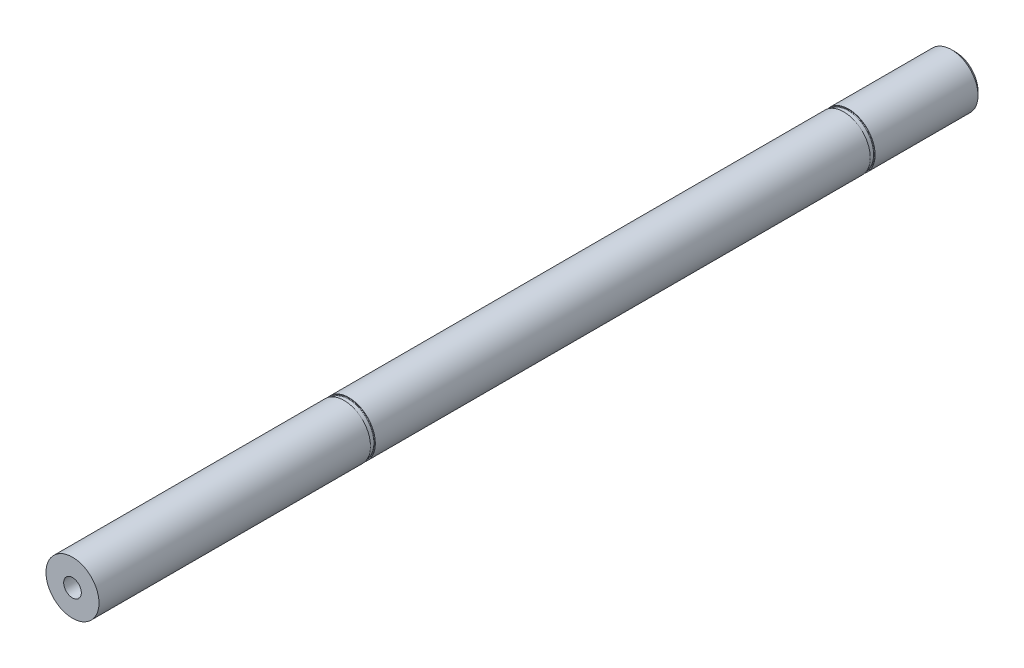
SolidWorks part; units mm, degrees
material "AISI 1045 Steel, cold drawn"
ref_plane "Front" through (0, 0, 0) normal (0, 0, 1) x (1, 0, 0)
ref_plane "Top" through (0, 0, 0) normal (0, 1, 0) x (1, 0, 0)
ref_plane "Right" through (0, 0, 0) normal (1, 0, 0) x (0, 0, -1)
sketch "Sketch1" plane through (0, 0, 0) normal (0, 0, 1) x (1, 0, 0)
  circle A0 centre (0, 0) radius 6
  dimension "OD" = 12
extrude "Extrude1" add sketch "Sketch1" along normal mid plane 200
chamfer "Chamfer1" distance 0.9 angle 45 1 edges at (6, 0, -100)
sketch "Sketch2" plane through (0, 0, 0) normal (0, 0, 1) x (1, 0, 0)
  circle A0 centre (0, 0) radius 2
  dimension "ID" = 4
extrude "Extrude3" cut sketch "Sketch2" against normal through all and the other way through all
ref_plane "Plane1" through (0, 6, 0) normal (0, 1, 0) x (1, 0, 0)
ref_plane "Plane2" through (0, 0, 100) normal (-1, 0, 0) x (0, 1, 0)
sketch "Sketch5" plane through (0, 0, 100) normal (-1, 0, 0) x (0, 1, 0)
  line L0 (5.86, 61.5) -> (7.2, 61.5)
  line L1 (7.2, 61.5) -> (7.2, 62.6)
  line L2 (7.2, 62.6) -> (5.86, 62.6)
  line L3 (5.75, 62.49) -> (5.75, 61.61)
  line L4 (0, -50) -> (0, 50) construction
  line L6 (-6, 0) -> (6, 0) construction
  arc A0 (5.75, 61.61) -> (5.86, 61.5) centre (5.86, 61.61) ccw
  arc A1 (5.75, 62.49) -> (5.86, 62.6) centre (5.86, 62.49) cw
  point P13 (2.575, 0)
  dimension "D1" = 0.11
  dimension "D2" = 0.11
  dimension "D3" = 61.5
revolve "Groove for DIN 471 - 12 x 1, Circlip for shafts - normal1" cut sketch "Sketch5"
ref_plane "Plane3" through (0, 0, 100) normal (-1, 0, 0) x (0, 1, 0)
ref_plane "Plane4" through (0, 0, 100) normal (-1, 0, 0) x (0, 1, 0)
ref_plane "Plane5" through (0, 0, 100) normal (-1, 0, 0) x (0, 1, 0)
ref_plane "Plane6" through (0, 0, 100) normal (-1, 0, 0) x (0, 1, 0)
sketch "Sketch13" plane through (0, 0, 100) normal (-1, 0, 0) x (0, 1, 0)
  line L0 (5.86, 174.7) -> (7.2, 174.7)
  line L1 (7.2, 174.7) -> (7.2, 175.8)
  line L2 (7.2, 175.8) -> (5.86, 175.8)
  line L3 (5.75, 175.69) -> (5.75, 174.81)
  line L4 (0, -50) -> (0, 50) construction
  line L6 (-6, 62.6) -> (6, 62.6) construction
  arc A0 (5.75, 174.81) -> (5.86, 174.7) centre (5.86, 174.81) ccw
  arc A1 (5.75, 175.69) -> (5.86, 175.8) centre (5.86, 175.69) cw
  dimension "D1" = 0.11
  dimension "D2" = 0.11
  dimension "D3" = 112.1
revolve "Groove for DIN 471 - 12 x 1, Circlip for shafts - normal2" cut sketch "Sketch13"
equation "\"D1@Chamfer1\" = \"OD@Sketch1\" * .075"
